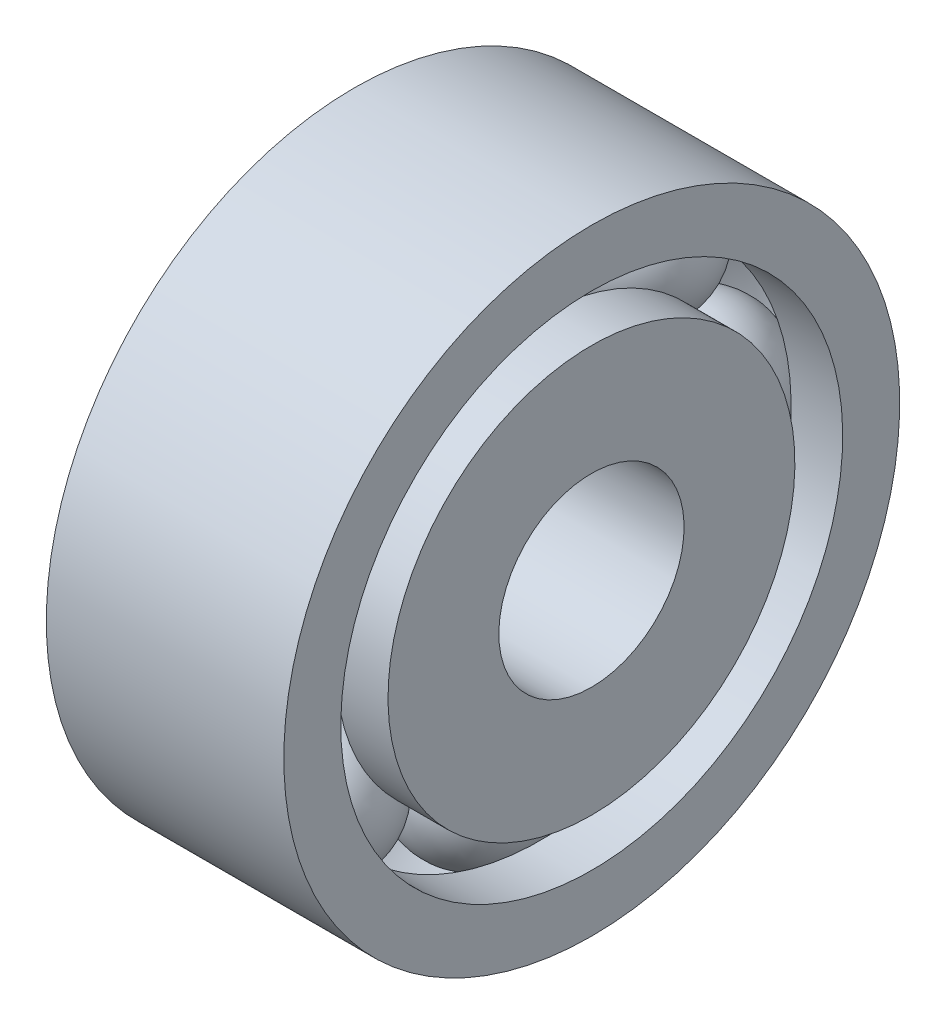
SolidWorks part; units mm, degrees
ref_plane "Front Plane" through (0, 0, 0) normal (0, 0, 1) x (1, 0, 0)
ref_plane "Top Plane" through (0, 0, 0) normal (0, 1, 0) x (1, 0, 0)
ref_plane "Right Plane" through (0, 0, 0) normal (1, 0, 0) x (0, 0, -1)
sketch "Sketch1" plane through (0, 0, 0) normal (0, 0, 1) x (1, 0, 0)
  line L0 (-6.3338, 0) -> (14.2055, 0) construction
  line L1 (-6.3338, 12.1485) -> (-6.3338, 16.4665)
  line L2 (-6.3338, 16.4665) -> (6.3662, 16.4665)
  line L3 (6.3662, 16.4665) -> (6.3662, 12.1485)
  line L4 (-6.3338, 12.1485) -> (6.3662, 12.1485)
  line L5 (-4.8435, 13.4185) -> (-4.8435, 12.1485) construction
  line L6 (-4.8435, 12.1485) -> (-4.8435, 11.4178) construction
  line L7 (-4.8435, 11.4178) -> (-3.7938, 12.1485) construction
  line L8 (-4.8435, 11.4178) -> (-5.8932, 12.1485) construction
  line L9 (0.0162, 15.9585) -> (0.0162, 12.1485) construction
  line L10 (-6.3338, 13.4185) -> (6.3662, 13.4185)
  line L11 (0.0162, 12.1485) -> (0, 0) construction
  circle A1 centre (0.0162, 12.1485) radius 3.81
  spline S0 degree 2 poles (-3.7938, 12.1485) (-4.8435, 14.6885) (-5.8932, 12.1485) knots 0 0 0 1 1 1
  spline S1 degree 2 poles (3.8262, 12.1485) (4.876, 14.6885) (5.9257, 12.1485) knots 0 0 0 1 1 1
  point P6 (3.9359, 0)
  dimension "D1" = 7.62
  dimension "D2" = 12.7
  dimension "D4" = 12.1485
  dimension "D5" = 1.27
  dimension "D6" = 4.318
revolve "Revolve1" add sketch "Sketch1" angle 360 about L0
sketch "Sketch4" plane through (0, 0, 0) normal (0, 0, 1) x (1, 0, 0)
  line L3 (-6.35, 4.953) -> (-6.35, 10.8785)
  line L5 (6.35, 10.8785) -> (6.35, 4.953)
  line L6 (0, 12.1485) -> (0, 0) construction
  line L7 (6.35, 0) -> (-6.35, 0) construction
  line L9 (-6.35, 4.953) -> (6.35, 4.953)
  line L12 (-6.35, 10.8785) -> (6.35, 10.8785)
  line L13 (-6.35, 10.8785) -> (-6.35, 4.953)
  line L21 (6.35, 10.8785) -> (6.35, 4.953)
  circle A1 centre (0, 12.1485) radius 3.81
  point P0 (0, 0)
  point P13 (0, 0)
  dimension "D3" = 7.62
  dimension "D1" = 12.1485
  dimension "D2" = 1.27
  dimension "D4" = 4.953
  dimension "D5" = 5.9255
  dimension "D7" = 12.7
revolve "Revolve2" add sketch "Sketch4" angle 360 about L7
sketch "Sketch5" plane through (0, 0, 0) normal (0, 0, 1) x (1, 0, 0)
  line L0 (0, 0) -> (0, 12.1485) construction
  line L2 (0, 8.402) -> (0, 15.895)
  arc A0 (0, 8.402) -> (0, 15.895) centre (0, 12.1485) ccw
  dimension "D2" = 7.493
  dimension "D1" = 12.1485
revolve "Revolve5" add sketch "Sketch5" angle 360 about L0
pattern_circular "CirPattern2" count 8 over 360 about axis through (0, 0, 0) along (1, 0, 0) of bodies 104
